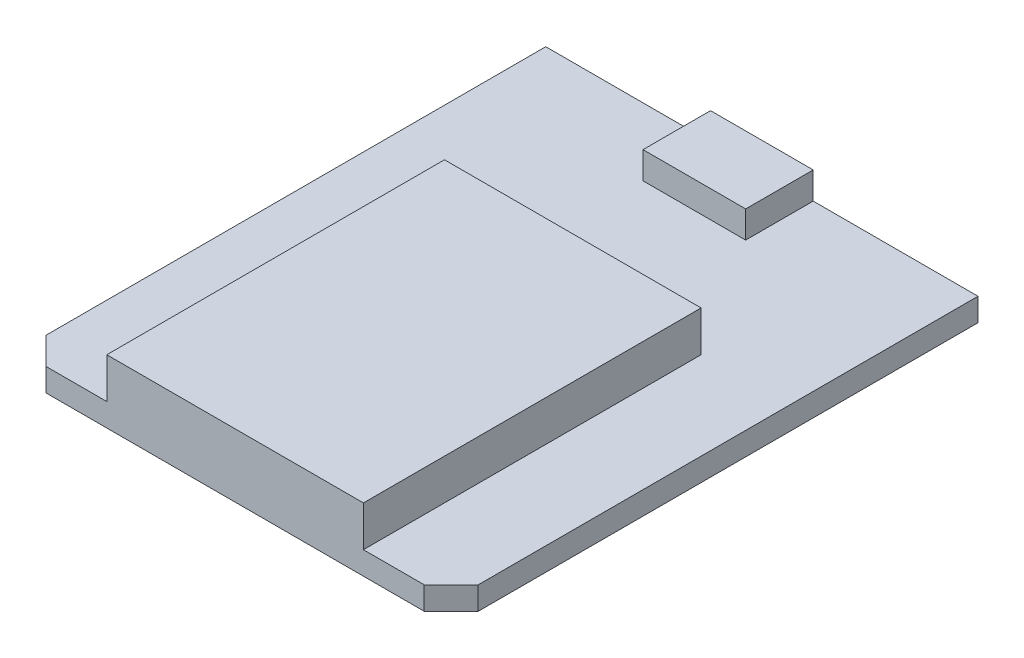
SolidWorks part; units mm, degrees
ref_plane "Front Plane" through (0, 0, 0) normal (0, 0, 1) x (1, 0, 0)
ref_plane "Top Plane" through (0, 0, 0) normal (0, 1, 0) x (1, 0, 0)
ref_plane "Right Plane" through (0, 0, 0) normal (1, 0, 0) x (0, 0, -1)
sketch "Sketch1" plane through (0, 0, 0) normal (0, 1, 0) x (1, 0, 0)
  line L1 (0, 0) -> (32, 0)
  line L2 (0, 0) -> (0, 39)
  line L3 (0, 39) -> (32, 39)
  line L4 (32, 0) -> (32, 39)
  dimension "D1" = 39
  dimension "D2" = 32
extrude "Boss-Extrude1" add sketch "Sketch1" along normal blind 1.7
chamfer "Chamfer1" distance 2 angle 45 2 edges at (32, 0.85, 0) (0, 0.85, 0)
sketch "Sketch3" plane through (0, 1.7, 0) normal (0, 1, 0) x (1, 0, 0)
  line L0 (2, 0) -> (30, 0) construction
  line L1 (6.5, 0) -> (25.5, 0)
  line L2 (6.5, 0) -> (6.5, 25)
  line L3 (6.5, 25) -> (25.5, 25)
  line L4 (25.5, 0) -> (25.5, 25)
  point P6 (6.6003, 25.6449)
  point P7 (28.6139, 0)
  point P8 (35.7447, 0)
  point P9 (16, 0)
  point P10 (16, 0)
  dimension "D1" = 19
  dimension "D2" = 25
extrude "Boss-Extrude2" add sketch "Sketch3" along normal blind 3
sketch "Sketch4" plane through (0, 1.7, 0) normal (0, 1, 0) x (1, 0, 0)
  line L0 (32, 39) -> (0, 39) construction
  line L1 (12.2, 39) -> (19.8, 39)
  line L2 (12.2, 39) -> (12.2, 34)
  line L3 (12.2, 34) -> (19.8, 34)
  line L4 (19.8, 39) -> (19.8, 34)
  point P6 (-7.2614, 39)
  point P7 (7.7003, 39)
  point P8 (16, 39)
  point P9 (16, 39)
  point P10 (12.1971, 33.905)
  dimension "D1" = 5
  dimension "D2" = 7.6
extrude "Boss-Extrude3" add sketch "Sketch4" along normal blind 2
